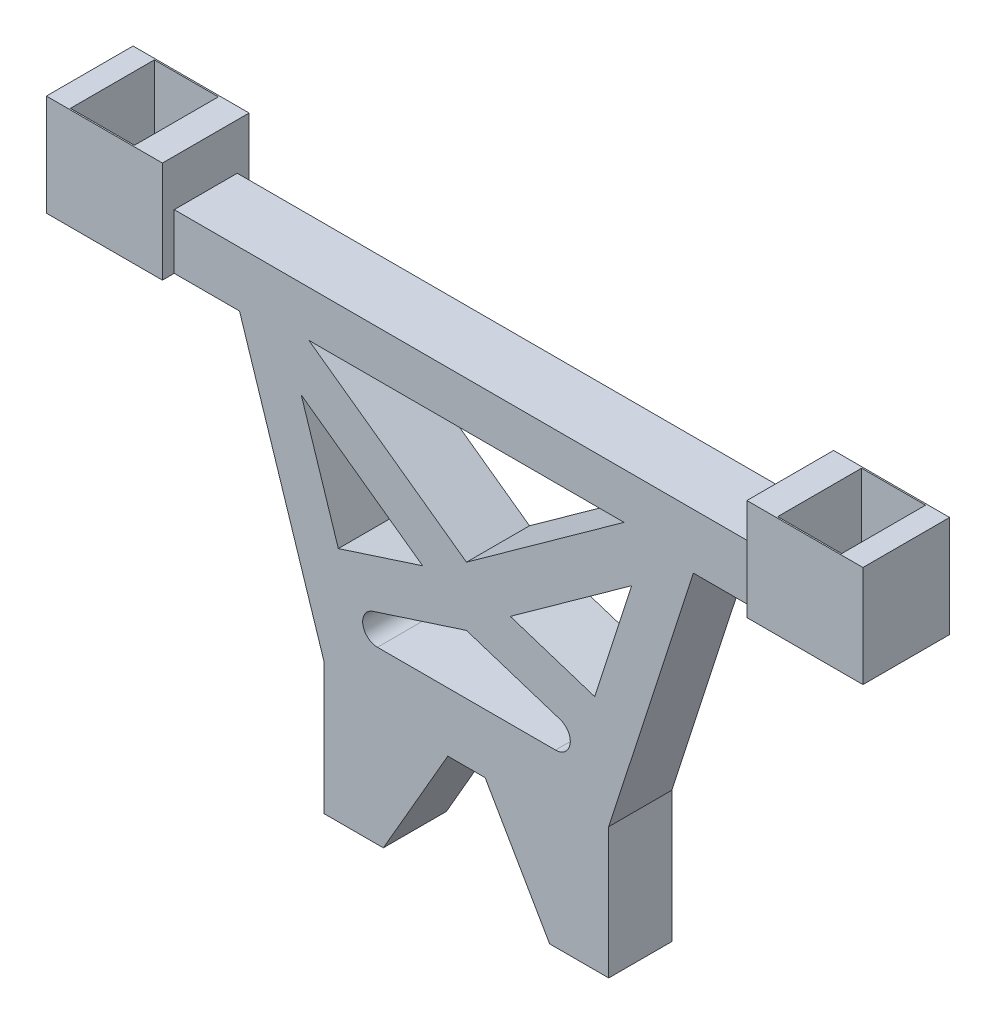
SolidWorks part; units mm, degrees
ref_plane "Front Plane" through (0, 0, 0) normal (0, 0, 1) x (1, 0, 0)
ref_plane "Top Plane" through (0, 0, 0) normal (0, 1, 0) x (1, 0, 0)
ref_plane "Right Plane" through (0, 0, 0) normal (1, 0, 0) x (0, 0, -1)
sketch "Sketch1" plane through (0, 0, 0) normal (0, 0, 1) x (1, 0, 0)
  line L0 (0, -1000) -> (0, 49000) construction
  line L1 (37.6809, 28.1432) -> (-37.6809, 28.1432)
  line L2 (-37.6809, 28.1432) -> (-37.6809, 34.1092)
  line L3 (-37.6809, 34.1092) -> (-52.6415, 34.1092)
  line L4 (-52.6415, 34.1092) -> (-52.6415, 21.0282)
  line L5 (-52.6415, 21.0282) -> (-29.2631, 21.0282)
  line L6 (-29.2631, 21.0282) -> (-18.3412, -12.7426)
  line L7 (-18.3412, -12.7426) -> (-18.3412, -29.6418)
  line L8 (-18.3412, -29.6418) -> (-10.7212, -29.6418)
  line L9 (-10.7212, -29.6418) -> (-2.4064, -15.24)
  line L10 (-2.4064, -15.24) -> (2.4064, -15.24)
  line L11 (11.4803, -7.62) -> (-11.4803, -7.62)
  line L12 (-12.0665, -3.9024) -> (0, 0)
  line L13 (20.32, 22.225) -> (-20.32, 22.225)
  line L14 (-20.32, 22.225) -> (0, 7.62)
  line L15 (-21.3011, 15.6419) -> (-5.6501, 4.3927)
  line L16 (-5.6501, 4.3927) -> (-16.5255, 0.8755)
  line L17 (-16.5255, 0.8755) -> (-21.3011, 15.6419)
  line L18 (16.5255, 0.8755) -> (21.3011, 15.6419)
  line L19 (5.6501, 4.3927) -> (16.5255, 0.8755)
  line L20 (21.3011, 15.6419) -> (5.6501, 4.3927)
  line L21 (20.32, 22.225) -> (0, 7.62)
  line L22 (12.0665, -3.9024) -> (0, 0)
  line L23 (10.7212, -29.6418) -> (2.4064, -15.24)
  line L24 (18.3412, -29.6418) -> (10.7212, -29.6418)
  line L25 (18.3412, -12.7426) -> (18.3412, -29.6418)
  line L26 (29.2631, 21.0282) -> (18.3412, -12.7426)
  line L27 (52.6415, 21.0282) -> (29.2631, 21.0282)
  line L28 (52.6415, 34.1092) -> (52.6415, 21.0282)
  line L29 (37.6809, 34.1092) -> (52.6415, 34.1092)
  line L30 (37.6809, 28.1432) -> (37.6809, 34.1092)
  arc A0 (-11.4803, -7.62) -> (-12.0665, -3.9024) centre (-11.4803, -5.715) cw
  arc A1 (11.4803, -7.62) -> (12.0665, -3.9024) centre (11.4803, -5.715) ccw
  point P16 (0, -7.62)
  point P32 (0, 22.225)
  point P33 (0, -15.24)
  point P41 (0, 28.1432)
  dimension "D14" = 1.905
  dimension "D1" = 5.9182
  dimension "D2" = 5.9182
  dimension "D3" = 5.9182
  dimension "D4" = 5.9182
  dimension "D5" = 7.62
  dimension "D6" = 7.62
  dimension "D7" = 15.5194
  dimension "D8" = 14.605
  dimension "D9" = 57.785
  dimension "D10" = 20.32
  dimension "D11" = 11.43
  dimension "D12" = 60
  dimension "D13" = 7.62
  dimension "D15" = 13.081
  dimension "D16" = 14.9606
  dimension "D17" = 105.283
  dimension "D18" = 7.62
extrude "Boss-Extrude1" add sketch "Sketch1" along normal mid plane 11.176
sketch "Sketch2" plane through (0, 28.1432, 0) normal (0, 1, 0) x (1, 0, 0)
  line L0 (37.6809, -5.588) -> (37.6809, 5.588) construction
  line L1 (-37.6809, -5.588) -> (37.6809, -5.588)
  line L2 (-37.6809, -5.588) -> (-37.6809, -4.064)
  line L3 (-37.6809, -4.064) -> (37.6809, -4.064)
  line L4 (37.6809, -5.588) -> (37.6809, -4.064)
  line L5 (-1000, 0) -> (49000, 0) construction
  line L6 (37.6809, 5.588) -> (37.6809, 4.064)
  line L7 (-37.6809, 4.064) -> (37.6809, 4.064)
  line L8 (-37.6809, 5.588) -> (-37.6809, 4.064)
  line L9 (-37.6809, 5.588) -> (37.6809, 5.588)
  dimension "D1" = 8.128
extrude "Cut-Extrude1" cut sketch "Sketch2" against normal up to surface (57.785 mm away) up to face at (-14.5312, -29.6418, 0)
sketch "Sketch3" plane through (0, 34.1092, 0) normal (0, 1, 0) x (1, 0, 0)
  line L0 (0, -1000) -> (0, 49000) construction
  line L1 (-49.7205, 5.4102) -> (-41.4655, 5.4102)
  line L2 (-49.7205, 5.4102) -> (-49.7205, -5.4102)
  line L3 (-49.7205, -5.4102) -> (-41.4655, -5.4102)
  line L4 (-41.4655, 5.4102) -> (-41.4655, -5.4102)
  line L5 (41.4655, 5.4102) -> (41.4655, -5.4102)
  line L6 (49.7205, -5.4102) -> (41.4655, -5.4102)
  line L7 (49.7205, 5.4102) -> (49.7205, -5.4102)
  line L8 (49.7205, 5.4102) -> (41.4655, 5.4102)
  line L9 (-35.0631, 0) -> (35.0631, 0) construction
  line L10 (-52.6415, -5.588) -> (-52.6415, 5.588) construction
  point P11 (-49.7205, 0)
  dimension "D1" = 10.8204
  dimension "D2" = 8.255
  dimension "D3" = 2.921
extrude "Cut-Extrude2" cut sketch "Sketch3" against normal through all
